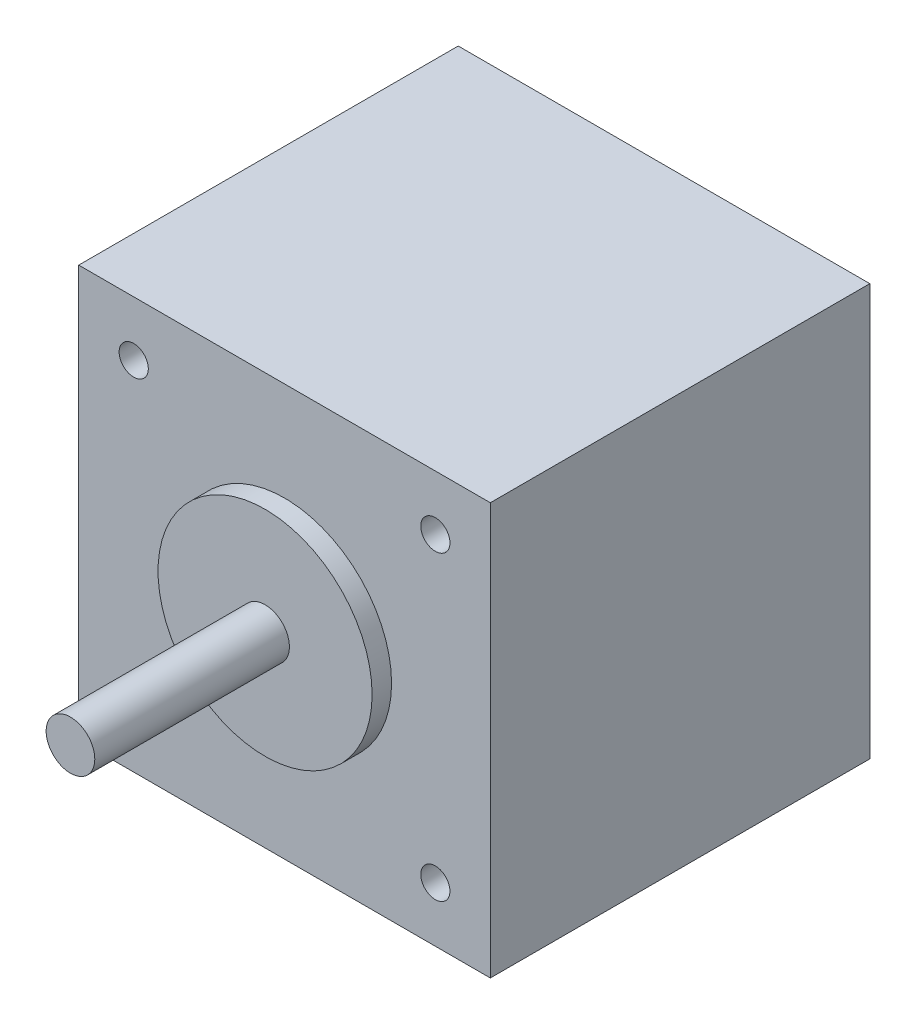
SolidWorks part; units mm, degrees
ref_plane "Ebene vorne" through (0, 0, 0) normal (0, 0, 1) x (1, 0, 0)
ref_plane "Ebene oben" through (0, 0, 0) normal (0, 1, 0) x (1, 0, 0)
ref_plane "Ebene rechts" through (0, 0, 0) normal (1, 0, 0) x (0, 0, -1)
sketch "Skizze1" plane through (0, 0, 0) normal (0, 0, 1) x (1, 0, 0)
  line L1 (-21.15, -21.15) -> (21.15, -21.15)
  line L2 (-21.15, -21.15) -> (-21.15, 21.15)
  line L3 (-21.15, 21.15) -> (21.15, 21.15)
  line L4 (21.15, -21.15) -> (21.15, 21.15)
  line L5 (-21.15, -21.15) -> (21.15, 21.15) construction
  line L6 (-21.15, 21.15) -> (21.15, -21.15) construction
  point P0 (0, 0)
  dimension "D1" = 42.3
extrude "Aufsatz-Linear austragen1" add sketch "Skizze1" along normal blind 39
sketch "Skizze2" plane through (0, 0, 39) normal (0, 0, 1) x (1, 0, 0)
  circle A0 centre (0, 0) radius 11
  dimension "D1" = 22
extrude "Aufsatz-Linear austragen2" add sketch "Skizze2" along normal blind 2
sketch "Skizze3" plane through (0, 0, 41) normal (0, 0, 1) x (1, 0, 0)
  circle A0 centre (0, 0) radius 2.5
  dimension "D1" = 5
extrude "Aufsatz-Linear austragen3" add sketch "Skizze3" along normal blind 20
sketch "Skizze4" plane through (0, 0, 39) normal (0, 0, 1) x (1, 0, 0)
  line L1 (-15.5, -15.5) -> (15.5, -15.5) construction
  line L2 (-15.5, -15.5) -> (-15.5, 15.5) construction
  line L3 (-15.5, 15.5) -> (15.5, 15.5) construction
  line L4 (15.5, -15.5) -> (15.5, 15.5) construction
  line L5 (-15.5, -15.5) -> (15.5, 15.5) construction
  line L6 (-15.5, 15.5) -> (15.5, -15.5) construction
  circle A0 centre (-15.5, 15.5) radius 1.5
  circle A1 centre (15.5, 15.5) radius 1.5
  circle A2 centre (15.5, -15.5) radius 1.5
  circle A3 centre (-15.5, -15.5) radius 1.5
  point P0 (0, 0)
  dimension "D3" = 3
  dimension "D1" = 31
  dimension "D2" = 31
extrude "Schnitt-Linear austragen1" cut sketch "Skizze4" against normal blind 4
